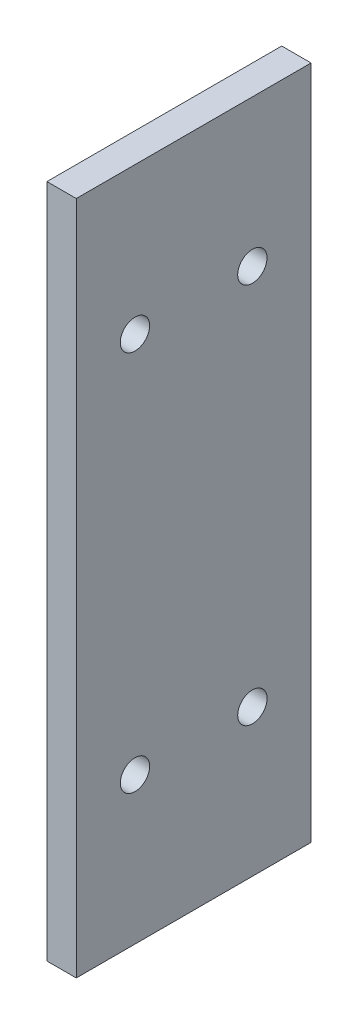
SolidWorks part; units mm, degrees
ref_plane "Front Plane" through (0, 0, 0) normal (1, 0, 0) x (0, 1, 0)
ref_plane "Top Plane" through (0, 0, 0) normal (0, 0, 1) x (0, 1, 0)
ref_plane "Right Plane" through (0, 0, 0) normal (0, 1, 0) x (-1, 0, 0)
sketch "Sketch1" plane through (0, 0, 0) normal (1, 0, 0) x (0, 1, 0)
  line L0 (-76.3514, 0) -> (77.4077, 0) construction
  line L1 (57.5, -20) -> (-57.5, -20)
  line L2 (57.5, -20) -> (57.5, 20)
  line L3 (57.5, 20) -> (-57.5, 20)
  line L4 (-57.5, -20) -> (-57.5, 20)
  line L5 (57.5, -20) -> (-57.5, 20) construction
  line L6 (57.5, 20) -> (-57.5, -20) construction
  line L7 (0, 31.2461) -> (0, -44.8918) construction
  circle A0 centre (-32.5, 10) radius 2.5
  circle A1 centre (32.5, 10) radius 2.5
  circle A2 centre (32.5, -10) radius 2.5
  circle A3 centre (-32.5, -10) radius 2.5
  point P0 (0, 0)
  dimension "D5" = 5
  dimension "D1" = 115
  dimension "D2" = 40
  dimension "D3" = 25
  dimension "D4" = 10
extrude "Boss-Extrude1" add sketch "Sketch1" along normal blind 5
